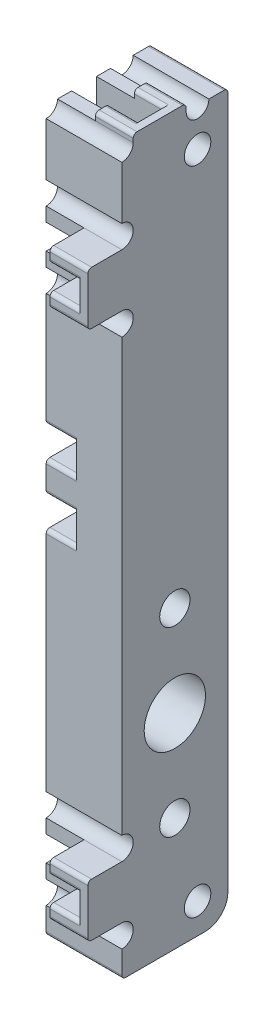
SolidWorks part; units mm, degrees
ref_plane "Front Plane" through (0, 0, 0) normal (0, 0, 1) x (1, 0, 0)
ref_plane "Top Plane" through (0, 0, 0) normal (0, 1, 0) x (1, 0, 0)
ref_plane "Right Plane" through (0, 0, 0) normal (1, 0, 0) x (0, 0, -1)
sketch "Sketch17" plane through (0, 0, 0) normal (1, 0, 0) x (0, 0, -1)
  line L0 (14, -60) -> (14, -95)
  line L1 (0, 0) -> (14, 0)
  line L2 (0, 0) -> (0, -95)
  line L3 (0, -95) -> (14, -95)
  line L4 (14, 0) -> (14, -45)
  line L5 (14, -45) -> (24, -45) construction
  line L6 (14, -45) -> (14, -60)
  line L7 (14, -60) -> (24, -60) construction
  line L8 (24, -45) -> (24, -60) construction
  dimension "D3" = 60
  dimension "D1" = 95
  dimension "D2" = 14
  dimension "D4" = 15
  dimension "D5" = 10
extrude "Boss-Extrude3" add sketch "Sketch17" along normal blind 10
sketch "Sketch19" plane through (0, 0, 0) normal (-1, 0, 0) x (0, 0, 1)
  line L0 (0, 0) -> (0, -95) construction
  line L1 (-14, 0) -> (0, 0) construction
  circle A0 centre (-7, -56) radius 2
  circle A1 centre (-7, -68) radius 4.05
  circle A2 centre (-7, -80) radius 2
  dimension "D1" = 4
  dimension "D2" = 8.1
  dimension "D3" = 12
  dimension "D4" = 68
  dimension "D5" = 7
  dimension "D6" = 12
extrude "Cut-Extrude13" cut sketch "Sketch19" against normal through all
sketch "Sketch24" plane through (0, 0, 0) normal (-1, 0, 0) x (0, 0, 1)
  line L0 (-14, 0) -> (0, 0) construction
  line L1 (-14, -95) -> (-14, 0) construction
  circle A0 centre (-10, -5) radius 1.75
  circle A1 centre (-10, -91) radius 1.75
  dimension "D1" = 3.5
  dimension "D2" = 5
  dimension "D3" = 4
  dimension "D4" = 86
extrude "Cut-Extrude17" cut sketch "Sketch24" against normal blind 10
sketch "Sketch30" plane through (10, 0, 0) normal (1, 0, 0) x (0, 0, -1)
  line L0 (0, 0) -> (0, -95) construction
  line L1 (0, -11.5) -> (-4.5, -11.5)
  line L2 (0, -11.5) -> (0, -18.5)
  line L3 (0, -18.5) -> (-4.5, -18.5)
  line L4 (-4.5, -11.5) -> (-4.5, -18.5)
  line L5 (0, 0) -> (0, -95) construction
  line L6 (0, -88.5) -> (-4.5, -88.5)
  line L7 (0, -88.5) -> (0, -81.5)
  line L8 (0, -81.5) -> (-4.5, -81.5)
  line L9 (-4.5, -88.5) -> (-4.5, -81.5)
  line L11 (-4.5, -85) -> (0, -85) construction
  line L12 (-4.5, -15) -> (0, -15) construction
  line L13 (14, 0) -> (0, 0) construction
  line L14 (5, 1) -> (5, 0) construction
  line L15 (1.5, 0) -> (8.5, 0)
  line L16 (1.5, 0) -> (1.5, 1)
  line L17 (1.5, 1) -> (8.5, 1)
  line L18 (8.5, 0) -> (8.5, 1)
  dimension "D1" = 4.5
  dimension "D2" = 7
  dimension "D3" = 15
  dimension "D4" = 70
  dimension "D5" = 7
  dimension "D6" = 1
  dimension "D7" = 5
extrude "Boss-Extrude4" add sketch "Sketch30" against normal blind 5
sketch "Sketch26" plane through (0, 0, 0) normal (-1, 0, 0) x (0, 0, 1)
  line L0 (-7, -15) -> (7, -15) construction
  line L1 (-7, -13.35) -> (7, -13.35)
  line L2 (-7, -16.65) -> (7, -16.65)
  line L3 (-7, -85) -> (7, -85) construction
  line L4 (-7, -83.35) -> (7, -83.35)
  line L5 (-7, -86.65) -> (7, -86.65)
  line L6 (-14, 0) -> (-8.5, 0) construction
  line L7 (0, 0) -> (0, -95) construction
  line L8 (-5, 8) -> (-5, -8) construction
  line L9 (-3.35, 8) -> (-3.35, -8)
  line L10 (-6.65, 8) -> (-6.65, -8)
  line L11 (-14, 0) -> (0, 0) construction
  arc A0 (-7, -13.35) -> (-7, -16.65) centre (-7, -15) ccw
  arc A1 (7, -16.65) -> (7, -13.35) centre (7, -15) ccw
  arc A2 (-7, -83.35) -> (-7, -86.65) centre (-7, -85) ccw
  arc A3 (7, -86.65) -> (7, -83.35) centre (7, -85) ccw
  arc A4 (-3.35, 8) -> (-6.65, 8) centre (-5, 8) ccw
  arc A5 (-6.65, -8) -> (-3.35, -8) centre (-5, -8) ccw
  point P2 (0, -15)
  point P7 (0, -85)
  point P14 (-11.25, 0)
  point P21 (-5, 0)
  dimension "D1" = 3.3
  dimension "D2" = 70
  dimension "D3" = 15
  dimension "D4" = 7
  dimension "D5" = 5
  dimension "D6" = 8
extrude "Cut-Extrude19" cut sketch "Sketch26" against normal blind 9
sketch "Sketch27" plane through (0, 0, 0) normal (-1, 0, 0) x (0, 0, 1)
  line L0 (-14, 0) -> (-6.65, 0) construction
  line L1 (-22.1814, -44.5) -> (2.3186, -44.5)
  line L2 (-22.1814, -44.5) -> (-22.1814, -48.5)
  line L3 (-22.1814, -36.5) -> (2.7477, -36.5)
  line L4 (-22.1814, -48.5) -> (2.3186, -48.5)
  line L5 (2.8186, -45) -> (2.8186, -48)
  line L6 (-22.1814, -36.5) -> (-22.1814, -40.5)
  line L7 (-22.1814, -40.5) -> (2.4686, -40.5)
  line L8 (2.8186, -36.5051) -> (2.8186, -39.6429)
  line L9 (-22.1814, -1046.5) -> (-22.1814, 48953.5) construction
  line L10 (2.8186, -1041.2533) -> (2.8186, 48958.7467) construction
  arc A0 (2.4686, -40.5) -> (2.8186, -39.6429) centre (2.4686, -40) ccw
  arc A1 (2.7477, -36.5) -> (2.8186, -36.5051) centre (2.7477, -37) cw
  arc A2 (2.3186, -48.5) -> (2.8186, -48) centre (2.3186, -48) ccw
  arc A3 (2.3186, -44.5) -> (2.8186, -45) centre (2.3186, -45) cw
  point P16 (-22.1814, -46.5)
  point P22 (-22.1814, -38.5)
  dimension "D1" = 4
  dimension "D6" = 0.5
  dimension "D2" = 46.5
  dimension "D3" = 25
  dimension "D4" = 8
  dimension "D5" = 4
extrude "Cut-Extrude21" cut sketch "Sketch27" against normal blind 4
sketch "Sketch31" plane through (10, 0, 0) normal (1, 0, 0) x (0, 0, -1)
  line L0 (0, -88.5) -> (0, -95) construction
  line L1 (0, -18.5) -> (0, -81.5) construction
  line L2 (0, 0) -> (0, -11.5) construction
  line L3 (14, 0) -> (8.5, 0) construction
  line L4 (8.5, 0) -> (8.5, 1) construction
  line L5 (1.5, 0) -> (0, 0) construction
  line L6 (1.5, 1) -> (1.5, 0) construction
  circle A0 centre (0, -90) radius 1.5
  circle A1 centre (0, -80) radius 1.5
  circle A2 centre (0, -20) radius 1.5
  circle A3 centre (0, -10) radius 1.5
  circle A4 centre (10, 0) radius 1.5
  circle A5 centre (0, 0) radius 1.5
  dimension "D1" = 3
  dimension "D2" = 3
  dimension "D3" = 3
extrude "Cut-Extrude24" cut sketch "Sketch31" against normal through all
sketch "Sketch29" plane through (0, 0, 0) normal (-1, 0, 0) x (0, 0, 1)
  circle A0 centre (-10, -5) radius 2
  circle A1 centre (-10, -91) radius 2
  dimension "D1" = 4
extrude "Cut-Extrude23" cut sketch "Sketch29" against normal blind 2
fillet "Fillet2" radius 0.5 22 edges at (2, -48.5, -14) (2, -44.5, -14) (2, -48.5, 0) (2, -44.5, 0) (5, 0, -14) (5, -95, 0) (2, -36.5, -14) (2, -40.5, -14) (2, -36.5, 0) (2, -40.5, 0) (7.5, 1, -8.5) (7, 1, -6.65) (7, 1, -3.35) (7.5, 1, -1.5) (7.5, -81.5, 4.5) (7, -83.35, 4.5) (7, -86.65, 4.5) (7.5, -88.5, 4.5) (7.5, -11.5, 4.5) (7.5, -18.5, 4.5) (7, -13.35, 4.5) (7, -16.65, 4.5)
fillet "Fillet1" radius 3 1 edges at (5, -95, -14)
